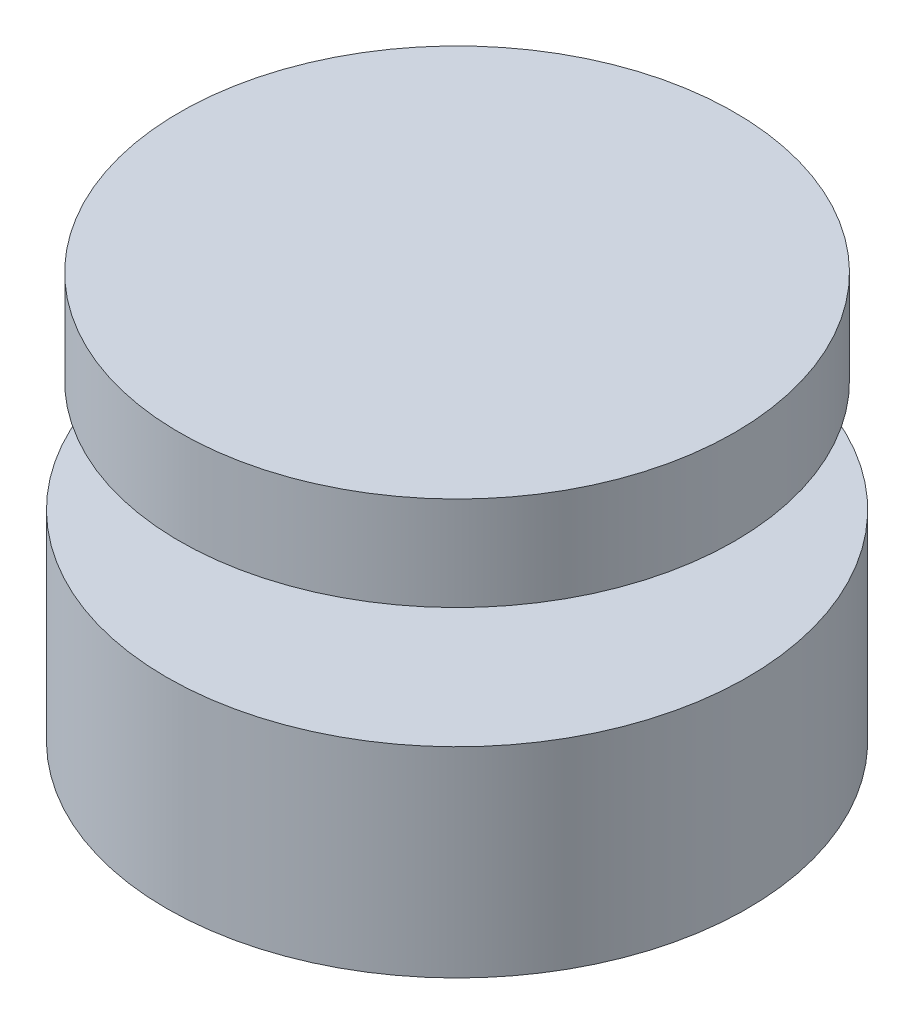
SolidWorks part; units mm, degrees
ref_plane "Front Plane" through (0, 0, 0) normal (0, 0, 1) x (1, 0, 0)
ref_plane "Top Plane" through (0, 0, 0) normal (0, 1, 0) x (1, 0, 0)
ref_plane "Right Plane" through (0, 0, 0) normal (1, 0, 0) x (0, 0, -1)
sketch "Sketch1" plane through (0, 0, 0) normal (0, 1, 0) x (1, 0, 0)
  circle A0 centre (0, 0) radius 2.9
  dimension "D1" = 5.8
extrude "Boss-Extrude1" add sketch "Sketch1" along normal blind 2
sketch "Sketch2" plane through (0, 0, 0) normal (0, -1, 0) x (1, 0, 0)
  circle A0 centre (0, 0) radius 2
  dimension "D1" = 4
extrude "Cut-Extrude1" cut sketch "Sketch2" against normal blind 1
sketch "Sketch3" plane through (0, 0, 0) normal (0, 0, 1) x (1, 0, 0)
  line L0 (-2.7714, 3.113) -> (-0.5474, 3.113)
  line L3 (-2.7714, 4.0517) -> (0, 4.0517)
  line L4 (-2.7714, 4.0517) -> (-2.7714, 3.113)
  line L7 (0, 2) -> (0, 4.0517)
  line L11 (-0.5474, 2) -> (0, 2)
  line L19 (-0.5474, 3.113) -> (-0.5474, 2)
  line L24 (2.9, 2) -> (-2.9, 2) construction
  point P9 (0, 3.113)
revolve "Revolve4" add sketch "Sketch3" angle 360 about L7
